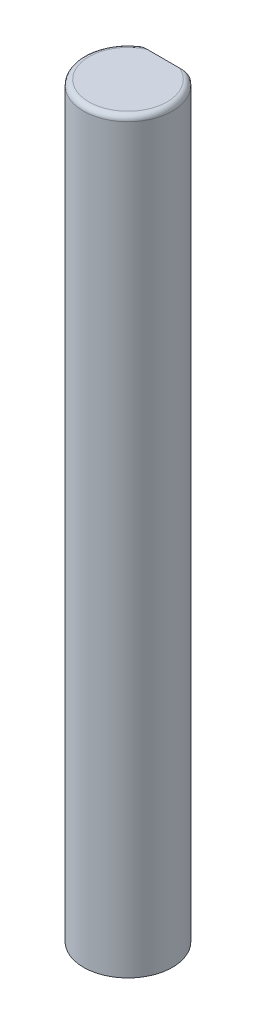
SolidWorks part; units mm, degrees
ref_plane "Front Plane" through (0, 0, 0) normal (0, 0, 1) x (1, 0, 0)
ref_plane "Top Plane" through (0, 0, 0) normal (0, 1, 0) x (1, 0, 0)
ref_plane "Right Plane" through (0, 0, 0) normal (1, 0, 0) x (0, 0, -1)
sketch "Sketch1" plane through (0, 0, 0) normal (0, 1, 0) x (1, 0, 0)
  circle A0 centre (0, 0) radius 2.5
  dimension "D1" = 5
extrude "Boss-Extrude1" add sketch "Sketch1" along normal blind 42
sketch "Sketch2" plane through (0, 42, 0) normal (0, 1, 0) x (1, 0, 0)
  line L1 (-4.1803, 2) -> (4.0513, 2)
  line L2 (-4.1803, 2) -> (-4.1803, 4.4772)
  line L3 (-4.1803, 4.4772) -> (4.0513, 4.4772)
  line L4 (4.0513, 2) -> (4.0513, 4.4772)
  circle A0 centre (0, 0) radius 2.5 construction
  dimension "D1" = 2
  dimension "D4" = 4.1803
  dimension "D2" = 2.4772
  dimension "D3" = 8.2316
extrude "Cut-Extrude1" cut sketch "Sketch2" against normal blind 18
fillet "Fillet1" radius 0.3 1 edges at (0, 42, 2.5)
